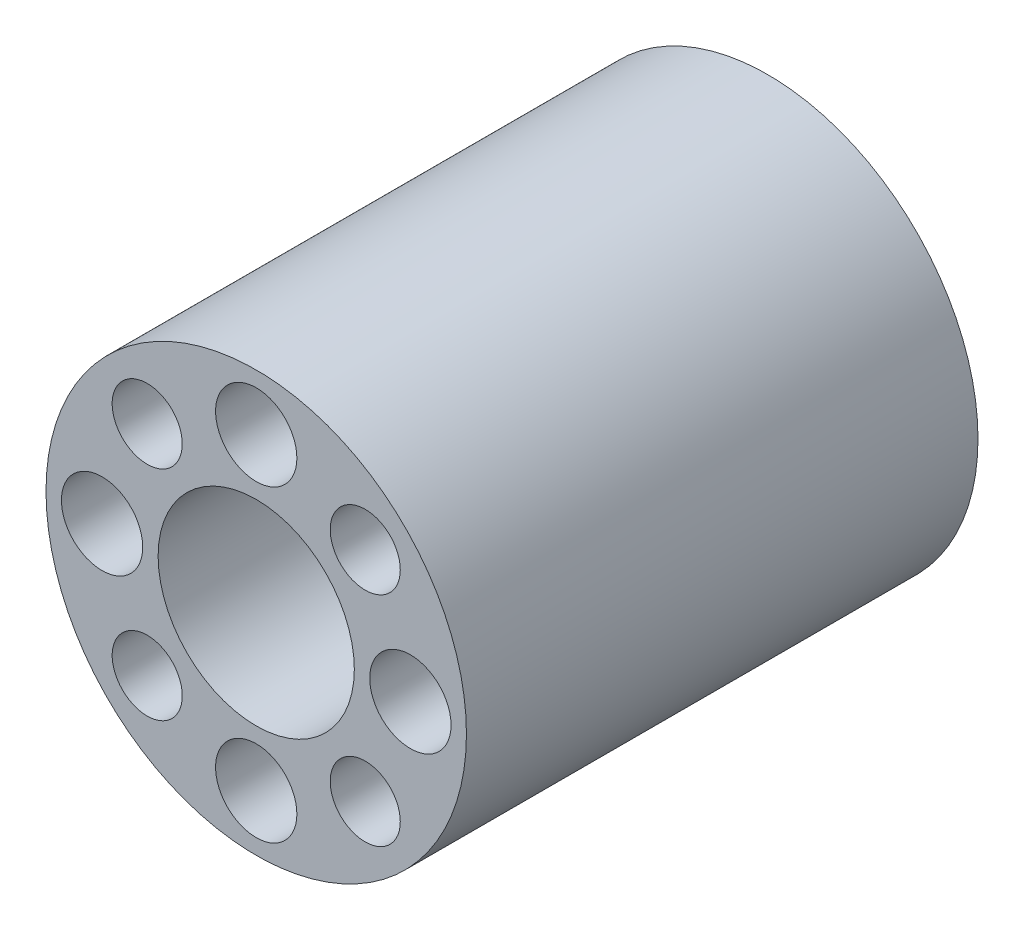
SolidWorks part; units mm, degrees
ref_plane "Ebene vorne" through (0, 0, 0) normal (0, 0, 1) x (1, 0, 0)
ref_plane "Ebene oben" through (0, 0, 0) normal (0, 1, 0) x (1, 0, 0)
ref_plane "Ebene rechts" through (0, 0, 0) normal (1, 0, 0) x (0, 0, -1)
sketch "Skizze1" plane through (0, 0, 0) normal (0, 0, 1) x (1, 0, 0)
  line L0 (-7, 0) -> (-15, 0) construction
  circle A0 centre (0, 0) radius 15
  circle A1 centre (0, 0) radius 7
  circle A2 centre (-11, 0) radius 1.65
  circle A3 centre (0, 11) radius 1.65
  circle A4 centre (11, 0) radius 1.65
  circle A5 centre (0, -11) radius 1.65
  point P8 (9.4975, 7.6461)
  point P9 (0, 0)
  point P20 (0, 0)
  dimension "D1" = 30
  dimension "D2" = 14
  dimension "D3" = 4
  dimension "D4" = 3.3
extrude "Aufsatz-Linear austragen1" add sketch "Skizze1" along normal blind 36.5
sketch "Skizze2" plane through (0, 0, 36.5) normal (0, 0, 1) x (1, 0, 0)
  line L0 (-7, 0) -> (-15, 0) construction
  circle A0 centre (0, 0) radius 7
  circle A1 centre (0, 0) radius 15
  circle A2 centre (-11, 0) radius 2.9
  circle A3 centre (0, 11) radius 2.9
  circle A4 centre (11, 0) radius 2.9
  circle A5 centre (0, -11) radius 2.9
  point P16 (0, 0)
  dimension "D1" = 5.8
  dimension "D2" = 4
extrude "Schnitt-Linear austragen1" cut sketch "Skizze2" against normal offset from surface (24.5 mm away) 12 contours A3 | A4 | A2 | A5 up to face at (15, 0, 0)
sketch "Skizze3" plane through (0, 0, 36.5) normal (0, 0, 1) x (1, 0, 0)
  line L0 (-4.9497, 4.9497) -> (-10.6066, 10.6066) construction
  circle A0 centre (0, 0) radius 7
  circle A1 centre (0, 0) radius 15
  circle A2 centre (-7.7782, 7.7782) radius 2.5
  circle A3 centre (7.7782, 7.7782) radius 2.5
  circle A4 centre (7.7782, -7.7782) radius 2.5
  circle A5 centre (-7.7782, -7.7782) radius 2.5
  point P16 (0, 0)
  dimension "D1" = 5
  dimension "D2" = 4
extrude "Schnitt-Linear austragen2" cut sketch "Skizze3" against normal blind 5 contours A2 | A3 | A4 | A5
